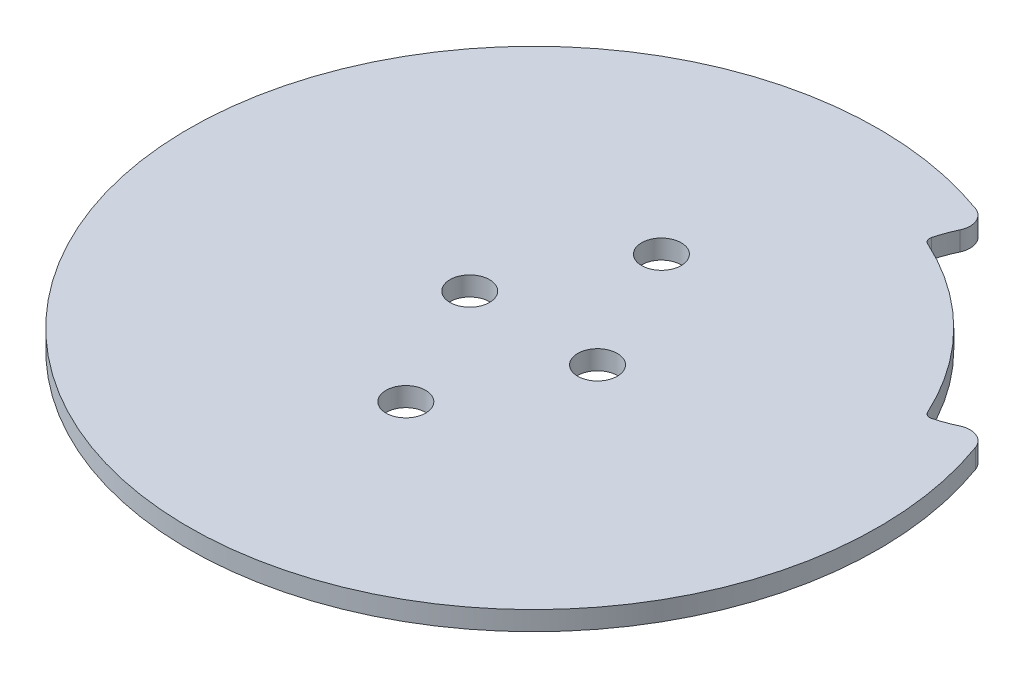
SolidWorks part; units mm, degrees
ref_plane "Front Plane" through (0, 0, 0) normal (0, 0, 1) x (1, 0, 0)
ref_plane "Top Plane" through (0, 0, 0) normal (0, 1, 0) x (1, 0, 0)
ref_plane "Right Plane" through (0, 0, 0) normal (1, 0, 0) x (0, 0, -1)
sketch "Sketch1" plane through (0, 0, 0) normal (0, 1, 0) x (1, 0, 0)
  line L0 (38.1838, 38.1838) -> (0, 0) construction
  line L1 (0, 0) -> (-49.6397, 0) construction
  circle A0 centre (0, 0) radius 54
  circle A1 centre (0, 0) radius 20 construction
  circle A2 centre (0, 20) radius 3.1
  circle A3 centre (0, -20) radius 3.1
  circle A4 centre (-10, 0) radius 3.1
  circle A5 centre (10, 0) radius 3.1
  circle A6 centre (0, 0) radius 10 construction
  circle A7 centre (38.1838, 38.1838) radius 20
  circle A8 centre (0, 0) radius 46.5
  dimension "D1" = 6.2
  dimension "D2" = 40
  dimension "D3" = 108
  dimension "D4" = 20
  dimension "D5" = 6.2
  dimension "D7" = 40
  dimension "D8" = 93
  dimension "D6" = 135
extrude "Boss-Extrude1" add sketch "Sketch1" along normal blind 3 contours A8 A7 A0 | A7 A8 A5 A4 A3 A2 | A7 A8
fillet "Fillet1" radius 3 2 edges at (49.4624, 1.5, -21.6673) (21.6673, 1.5, -49.4624)
fillet "Fillet2" radius 1 2 edges at (18.6742, 1.5, -42.5855) (42.5855, 1.5, -18.6742)
